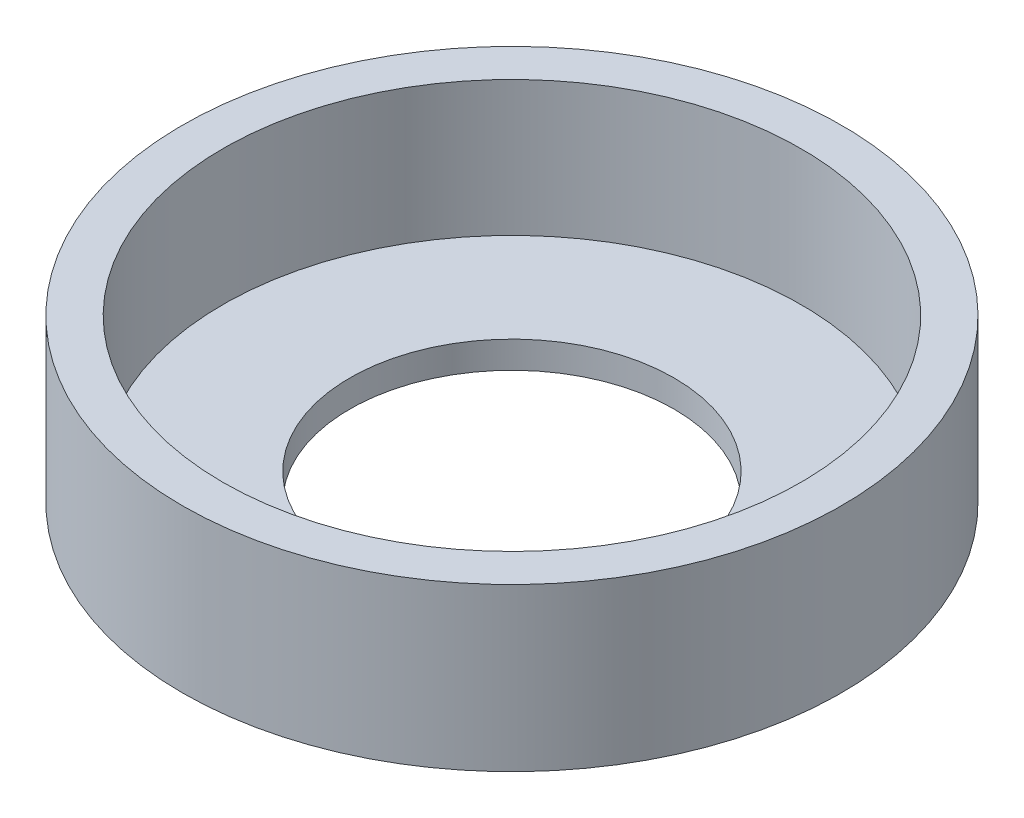
SolidWorks part; units mm, degrees
ref_plane "Front Plane" through (0, 0, 0) normal (0, 0, 1) x (1, 0, 0)
ref_plane "Top Plane" through (0, 0, 0) normal (0, 1, 0) x (1, 0, 0)
ref_plane "Right Plane" through (0, 0, 0) normal (1, 0, 0) x (0, 0, -1)
sketch "Sketch1" plane through (0, 0, 0) normal (1, 0, 0) x (0, 0, -1)
  line L0 (0, 27.0772) -> (0, -22.0037) construction
  line L1 (-12.2, 3) -> (-12.2, -3)
  line L2 (-12.2, -3) -> (-6, -3)
  line L3 (-6, -3) -> (-6, -2)
  line L4 (-6, -2) -> (-10.7, -2)
  line L5 (-10.7, -2) -> (-10.7, 3)
  line L6 (-10.7, 3) -> (-12.2, 3)
  point P5 (-12.2, 0)
  dimension "D1" = 6
  dimension "D2" = 1
  dimension "D3" = 21.4
  dimension "D4" = 12
  dimension "D5" = 1.5
revolve "Revolve1" add sketch "Sketch1" angle 360 about L0
